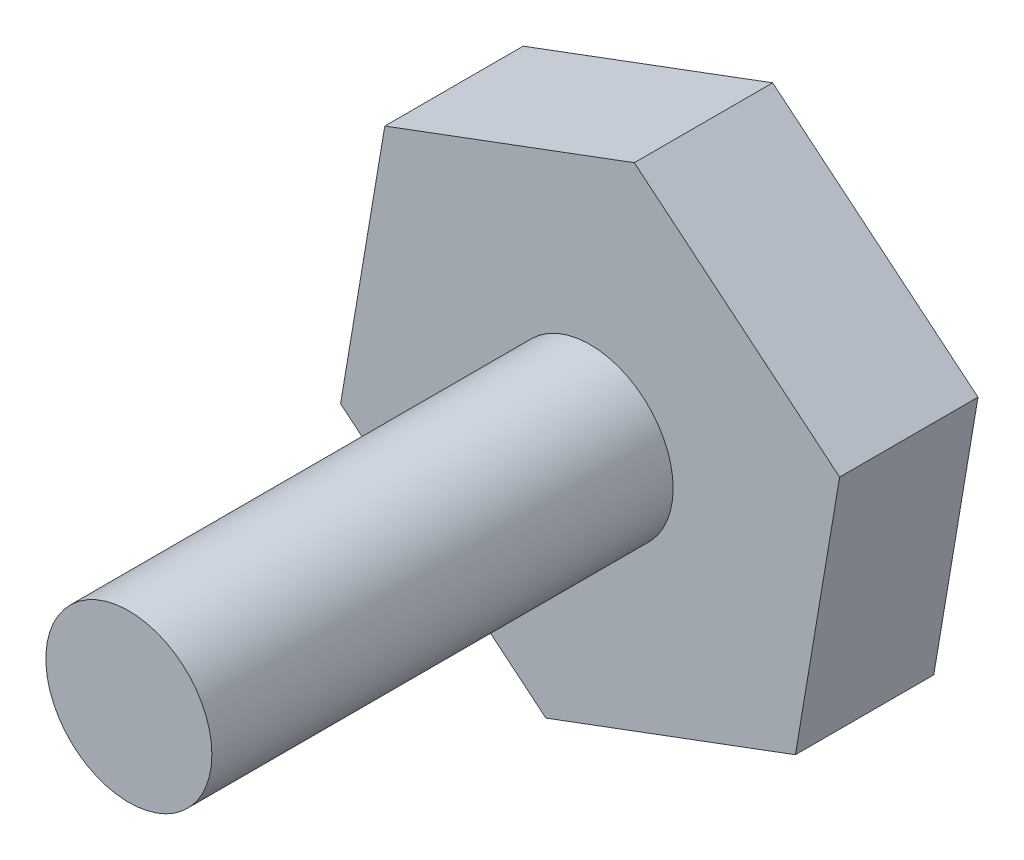
SolidWorks part; units mm, degrees
ref_plane "Plan de face" through (0, 0, 0) normal (0, 0, 1) x (1, 0, 0)
ref_plane "Plan de dessus" through (0, 0, 0) normal (0, 1, 0) x (1, 0, 0)
ref_plane "Plan de droite" through (0, 0, 0) normal (1, 0, 0) x (0, 0, -1)
sketch "Esquisse1" plane through (0, 0, 0) normal (0, 0, 1) x (1, 0, 0)
  line L1 (0.0907, 0.2094) -> (1.0496, 5.9027)
  line L2 (1.0496, 5.9027) -> (-3.4016, 9.5798)
  line L3 (-3.4016, 9.5798) -> (-8.8116, 7.5635)
  line L4 (-8.8116, 7.5635) -> (-9.7704, 1.8702)
  line L5 (-9.7704, 1.8702) -> (-5.3192, -1.8069)
  line L6 (-5.3192, -1.8069) -> (0.0907, 0.2094)
  circle A0 centre (-4.3604, 3.8864) radius 5 construction
extrude "Boss.-Extru.1" add sketch "Esquisse1" along normal blind 3
sketch "Esquisse2" plane through (0, 0, 3) normal (0, 0, 1) x (1, 0, 0)
  line L0 (-3.4016, 9.5798) -> (-8.8116, 7.5635) construction
  line L1 (-8.8116, 7.5635) -> (-9.7704, 1.8702) construction
  circle A0 centre (-4.3604, 3.8864) radius 1.8
  point P4 (0, 0)
  point P6 (-6.3224, 3.7059)
  dimension "D1" = 5
  dimension "D2" = 5
extrude "Boss.-Extru.2" add sketch "Esquisse2" along normal blind 10
